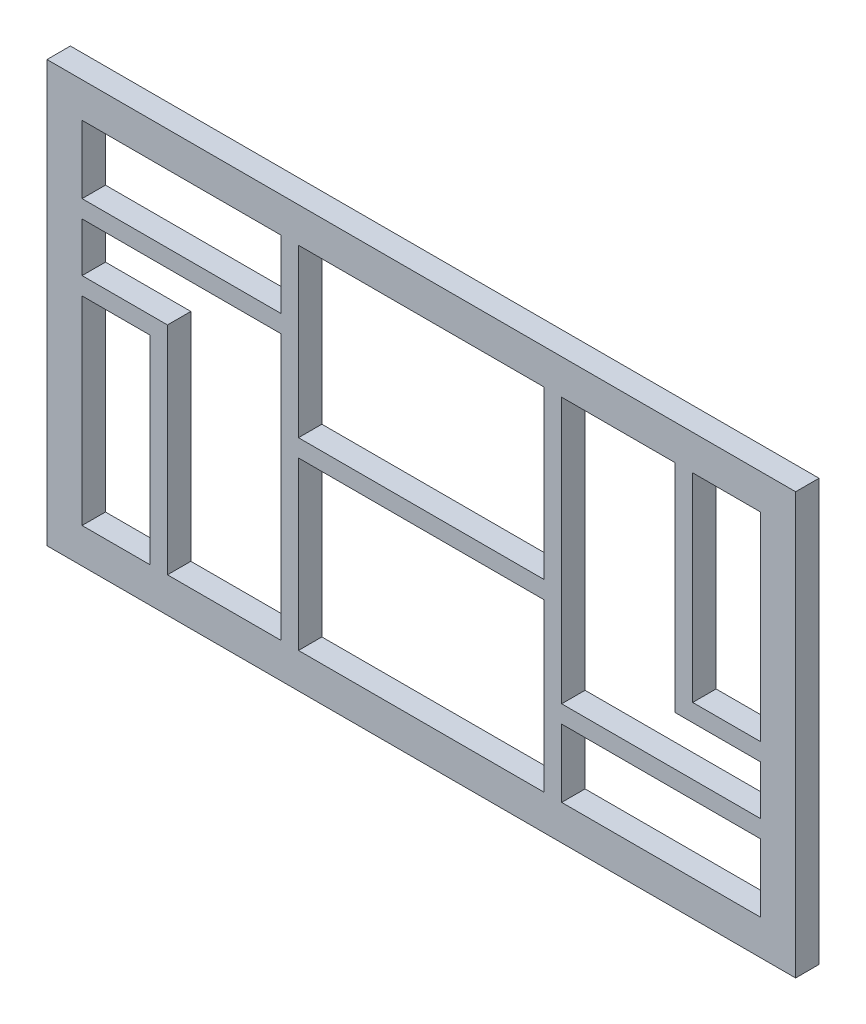
SolidWorks part; units mm, degrees
material "Eucalipto"
ref_plane "Plano frontal" through (0, 0, 0) normal (0, 0, 1) x (1, 0, 0)
ref_plane "Plano superior" through (0, 0, 0) normal (0, 1, 0) x (1, 0, 0)
ref_plane "Plano direito" through (0, 0, 0) normal (1, 0, 0) x (0, 0, -1)
sketch "Esboço1" plane through (0, 0, 0) normal (0, 0, 1) x (1, 0, 0)
  line L0 (215, 330) -> (425, 330)
  line L1 (0, 0) -> (640, 0)
  line L2 (0, 0) -> (0, 360)
  line L3 (0, 360) -> (640, 360)
  line L4 (640, 0) -> (640, 360)
  line L5 (30, 330) -> (200, 330)
  line L6 (30, 330) -> (30, 272)
  line L7 (30, 30) -> (88, 30)
  line L8 (610, 330) -> (610, 160)
  line L10 (200, 330) -> (200, 272)
  line L12 (215, 330) -> (215, 257)
  line L13 (200, 257) -> (30, 257)
  line L15 (200, 272) -> (30, 272)
  line L17 (30, 215) -> (88, 215)
  line L19 (30, 200) -> (88, 200)
  line L21 (88, 215) -> (103, 215)
  line L22 (88, 200) -> (88, 30)
  line L24 (103, 215) -> (103, 30)
  line L26 (425, 88) -> (425, 30)
  line L28 (440, 88) -> (440, 30)
  line L29 (440, 88) -> (610, 88)
  line L30 (425, 88) -> (425, 103)
  line L31 (440, 103) -> (610, 103)
  line L34 (537, 330) -> (537, 160)
  line L36 (552, 330) -> (552, 160)
  line L37 (552, 160) -> (610, 160)
  line L38 (537, 160) -> (537, 145)
  line L39 (537, 145) -> (610, 145)
  line L41 (30, 257) -> (30, 215)
  line L42 (103, 30) -> (200, 30)
  line L43 (30, 200) -> (30, 30)
  line L44 (440, 30) -> (610, 30)
  line L45 (610, 88) -> (610, 30)
  line L46 (610, 145) -> (610, 103)
  line L47 (552, 330) -> (610, 330)
  line L48 (215, 30) -> (425, 30)
  line L50 (200, 257) -> (200, 30)
  line L52 (215, 257) -> (215, 187.5)
  line L54 (425, 103) -> (425, 172.5)
  line L56 (440, 103) -> (440, 330)
  line L57 (440, 330) -> (537, 330)
  line L58 (0, 180) -> (640, 180) construction
  line L59 (215, 172.5) -> (215, 30)
  line L60 (215, 187.5) -> (425, 187.5)
  line L62 (215, 172.5) -> (425, 172.5)
  line L64 (425, 187.5) -> (425, 330)
  point P37 (103, 122.5)
  point P38 (425, 59)
  point P39 (552, 245)
  dimension "D1" = 640
  dimension "D2" = 360
  dimension "D3" = 30
  dimension "D4" = 30
  dimension "D5" = 30
  dimension "D6" = 30
  dimension "D7" = 15
  dimension "D8" = 15
  dimension "D9" = 15
  dimension "D10" = 15
  dimension "D11" = 15
  dimension "D12" = 15
  dimension "D13" = 15
  dimension "D14" = 15
  dimension "D15" = 170
  dimension "D16" = 58
  dimension "D17" = 170
  dimension "D18" = 58
  dimension "D19" = 170
  dimension "D20" = 58
  dimension "D21" = 170
  dimension "D22" = 58
  dimension "D23" = 15
  dimension "D24" = 15
  dimension "D25" = 15
  dimension "D26" = 15
  dimension "D27" = 15
  dimension "D28" = 15
  dimension "D29" = 15
  dimension "D30" = 7.5
  dimension "D31" = 7.5
extrude "Ressalto-extrusão1" add sketch "Esboço1" along normal blind 20
sketch "Esboço2" plane through (0, 0, 0) normal (0, 0, -1) x (-1, 0, 0)
  circle A0 centre (-179, 337.5) radius 4
  circle A1 centre (-179, 264.5) radius 4
  circle A2 centre (-22.5, 179) radius 4
  circle A3 centre (-95.5, 179) radius 4
  circle A4 centre (-461, 95.5) radius 4
  circle A5 centre (-461, 22.5) radius 4
  circle A6 centre (-544.5, 181) radius 4
  circle A7 centre (-617.5, 181) radius 4
  dimension "D1" = 8
  dimension "D2" = 8
  dimension "D3" = 8
  dimension "D4" = 8
  dimension "D5" = 8
  dimension "D6" = 8
  dimension "D7" = 8
  dimension "D8" = 8
extrude "Corte-extrusão1" cut sketch "Esboço2" against normal blind 15
